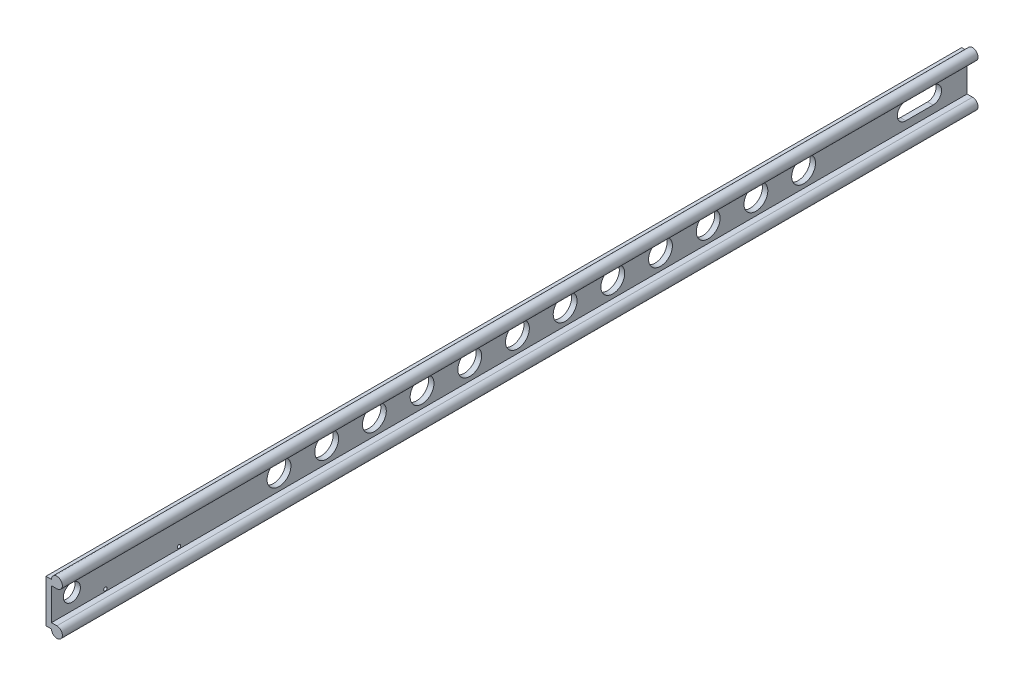
SolidWorks part; units mm, degrees
material "1060 Alloy"
ref_plane "Front Plane" through (0, 0, 0) normal (0, 0, 1) x (1, 0, 0)
ref_plane "Top Plane" through (0, 0, 0) normal (0, 1, 0) x (1, 0, 0)
ref_plane "Right Plane" through (0, 0, 0) normal (1, 0, 0) x (0, 0, -1)
sketch "Sketch1" plane through (0, 0, 0) normal (0, 0, 1) x (1, 0, 0)
  line L0 (-13.1544, 15.9067) -> (-8.0744, 15.9067)
  line L2 (-13.1544, 15.9067) -> (-13.1544, -24.0983)
  line L4 (-8.0744, 10.8267) -> (-8.0744, -19.0183)
  line L5 (-13.1544, -24.0983) -> (-8.0744, -24.0983)
  line L6 (-2.9944, -19.0183) -> (-8.0744, -19.0183)
  line L7 (-2.9944, 10.8267) -> (-8.0744, 10.8267)
  arc A2 (-2.9944, 10.8267) -> (-8.0744, 15.9067) centre (-2.9944, 15.9067) ccw
  arc A3 (-8.0744, -24.0983) -> (-2.9944, -19.0183) centre (-2.9944, -24.0983) ccw
  dimension "D3" = 10.16
  dimension "D4" = 10.16
  dimension "D1" = 5.08
  dimension "D2" = 40.005
extrude "Boss-Extrude1" add sketch "Sketch1" along normal blind 853.44
sketch "Sketch2" plane through (-13.1544, 0, 0) normal (-1, 0, 0) x (0, 0, 1)
  line L1 (0, -55) -> (0, 55) construction
  line L2 (853.44, 15.9067) -> (0, 15.9067) construction
  circle A0 centre (152.4, -4.0958) radius 11.1125
  dimension "D1" = 20.0025
  dimension "D3" = 22.225
  dimension "D2" = 152.4
extrude "Cut-Extrude1" cut sketch "Sketch2" against normal blind 25.4
pattern_linear "LPattern1" count 12 spacing 44.45 along (0, 0, 1) of "Cut-Extrude1"
sketch "Sketch3" plane through (-13.1544, 0, 0) normal (-1, 0, 0) x (0, 0, 1)
  line L0 (853.44, 15.9067) -> (0, 15.9067) construction
  line L1 (0, -8.382) -> (0, 8.382) construction
  line L3 (853.44, 15.9067) -> (853.44, -24.0983) construction
  line L4 (31.75, 3.8417) -> (57.15, 3.8417)
  line L5 (31.75, -12.0333) -> (57.15, -12.0333)
  circle A1 centre (834.39, -4.0958) radius 7.9375
  arc A2 (31.75, 3.8417) -> (31.75, -12.0333) centre (31.75, -4.0958) ccw
  arc A3 (57.15, 3.8417) -> (57.15, -12.0333) centre (57.15, -4.0958) cw
  dimension "D1" = 31.75
  dimension "D3" = 15.875
  dimension "D6" = 25.4
  dimension "D7" = 7.9375
  dimension "D2" = 20.0025
  dimension "D4" = 20.0025
  dimension "D5" = 19.05
extrude "Cut-Extrude2" cut sketch "Sketch3" against normal blind 25.4
sketch "Sketch5" plane through (-13.1544, 0, 0) normal (-1, 0, 0) x (0, 0, 1)
  line L0 (853.44, 15.9067) -> (0, 15.9067) construction
  line L1 (853.44, -24.0983) -> (0, -24.0983) construction
  line L2 (853.44, 15.9067) -> (853.44, -24.0983) construction
  circle A0 centre (734.568, 8.7947) radius 1.5875
  circle A1 centre (808.228, 8.7947) radius 1.5875
  circle A2 centre (803.148, -16.9863) radius 1.5875
  circle A3 centre (734.568, -16.9863) radius 1.5875
  dimension "D1" = 3.175
  dimension "D2" = 7.112
  dimension "D3" = 7.112
  dimension "D4" = 45.212
  dimension "D5" = 118.872
  dimension "D6" = 50.292
extrude "Cut-Extrude3" cut sketch "Sketch5" against normal blind 12.7
